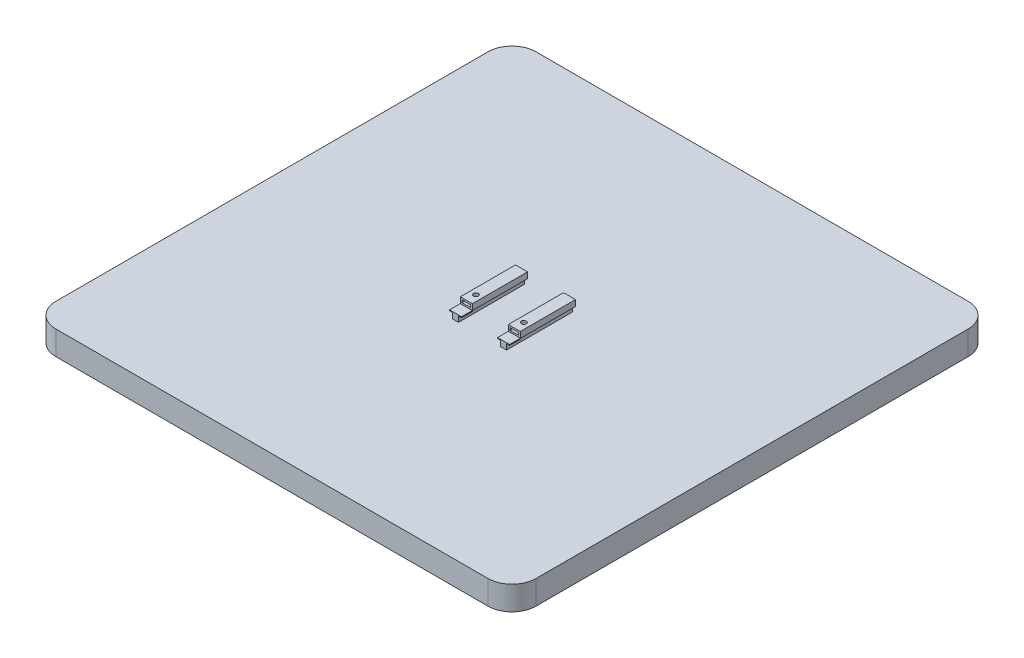
SolidWorks part; units mm, degrees
ref_plane "Front Plane" through (0, 0, 0) normal (0, 0, 1) x (1, 0, 0)
ref_plane "Top Plane" through (0, 0, 0) normal (0, 1, 0) x (1, 0, 0)
ref_plane "Right Plane" through (0, 0, 0) normal (1, 0, 0) x (0, 0, -1)
sketch "Sketch1" plane through (0, 0, 0) normal (0, 1, 0) x (1, 0, 0)
  line L1 (100, 100) -> (-100, 100)
  line L2 (100, 100) -> (100, -100)
  line L3 (100, -100) -> (-100, -100)
  line L4 (-100, 100) -> (-100, -100)
  line L5 (100, 100) -> (-100, -100) construction
  line L6 (100, -100) -> (-100, 100) construction
  point P0 (0, 0)
  dimension "D1" = 200
  dimension "D2" = 200
extrude "Boss-Extrude1" add sketch "Sketch1" along normal blind 10
ref_plane "Plane1" through (0, 0, 0) normal (0, 0, 1) x (1, 0, 0)
shell "Shell5" thickness 3
sketch "Sketch2" plane through (0, 0, 0) normal (0, 0, 1) x (1, 0, 0)
  line L0 (-11.0348, 10) -> (-11.0348, 12.6)
  line L1 (-11.0348, 12.6) -> (-12.2848, 12.6)
  line L2 (-12.2848, 12.6) -> (-12.2848, 15.1)
  line L3 (-12.2848, 15.1) -> (-7.2848, 15.1)
  line L4 (-7.2848, 15.1) -> (-7.2848, 12.6)
  line L5 (-7.2848, 12.6) -> (-8.5348, 12.6)
  line L6 (-8.5348, 12.6) -> (-8.5348, 10)
  line L7 (-8.5348, 10) -> (-11.0348, 10)
  line L8 (-9.7848, -37.9156) -> (-9.7848, 37.9156) construction
  line L9 (0.2152, -37.9156) -> (0.2152, 37.9156) construction
  line L10 (8.9652, 10) -> (11.4652, 10)
  line L11 (8.9652, 12.6) -> (8.9652, 10)
  line L12 (7.7152, 12.6) -> (8.9652, 12.6)
  line L13 (7.7152, 15.1) -> (7.7152, 12.6)
  line L14 (12.7152, 15.1) -> (7.7152, 15.1)
  line L15 (12.7152, 12.6) -> (12.7152, 15.1)
  line L16 (11.4652, 12.6) -> (12.7152, 12.6)
  line L17 (11.4652, 10) -> (11.4652, 12.6)
  line L18 (-100, 10) -> (100, 10) construction
  dimension "D1" = 2.5
  dimension "D2" = 5
  dimension "D3" = 2.5
  dimension "D4" = 2.6
  dimension "D5" = 8.75
extrude "Boss-Extrude2" add sketch "Sketch2" along normal mid plane 27.5
ref_plane "Plane2" through (0, 0, 13.75) normal (0, 0, 1) x (1, 0, 0)
sketch "Sketch5" plane through (0, 0, 13.75) normal (0, 0, 1) x (1, 0, 0)
  line L0 (-35.5496, 37.074) -> (-35.5496, 52.2233) construction
  line L1 (16.343, 12.3) -> (-35.2888, 12.3)
  line L2 (16.343, 12.3) -> (16.343, 15.1)
  line L3 (16.343, 15.1) -> (-35.2888, 15.1)
  line L4 (-35.2888, 12.3) -> (-35.2888, 15.1)
  line L5 (-9.4729, 37.074) -> (-9.4729, 52.2233) construction
  line L6 (-5.3876, 13.7) -> (-37.0511, 13.7) construction
  line L7 (-2.6881, -52.2233) -> (-2.6881, -37.074) construction
  line L8 (43.1278, -47.5797) -> (-8.504, -47.5797)
  line L9 (43.1278, -47.5797) -> (43.1278, -44.7797)
  line L10 (43.1278, -44.7797) -> (-8.504, -44.7797)
  line L11 (-8.504, -47.5797) -> (-8.504, -44.7797)
  line L12 (17.3119, -52.2233) -> (17.3119, -37.074) construction
  line L13 (21.3972, -46.1797) -> (-10.2663, -46.1797) construction
  line L14 (-7.2848, 15.1) -> (-12.2848, 15.1) construction
  dimension "D1" = 2.8
extrude "Cut-Extrude1" cut sketch "Sketch5" against normal blind 4.5
ref_plane "Plane3" through (0, 12.3, 0) normal (0, 1, 0) x (1, 0, 0)
sketch "Sketch6" plane through (0, 12.3, 0) normal (0, 1, 0) x (1, 0, 0)
  line L0 (12.7152, -13.75) -> (7.7152, -13.75)
  line L1 (12.7152, -13.75) -> (12.7152, -9.25)
  line L2 (12.7152, -9.25) -> (7.7152, -9.25)
  line L3 (7.7152, -13.75) -> (7.7152, -9.25)
  line L4 (12.7152, -13.75) -> (7.7152, -9.25) construction
  line L5 (12.7152, -9.25) -> (7.7152, -13.75) construction
  line L6 (0.2152, -2.725) -> (0.2152, 2.1712) construction
  line L7 (-12.2848, -9.25) -> (-7.2848, -9.25)
  line L8 (-7.2848, -13.75) -> (-7.2848, -9.25)
  line L9 (-12.2848, -13.75) -> (-7.2848, -13.75)
  line L10 (-12.2848, -13.75) -> (-12.2848, -9.25)
  line L11 (-11.0348, -9.25) -> (-8.5348, -9.25) construction
  line L12 (-12.2848, -9.25) -> (-12.2848, 13.75) construction
  line L13 (7.7152, -9.25) -> (7.7152, 13.75) construction
  point P0 (10.2152, -11.5)
  dimension "D1" = 4.5
  dimension "D2" = 5
extrude "Boss-Extrude3" add sketch "Sketch6" along normal blind 0.35
ref_plane "Plane4" through (0, 0, 9.25) normal (0, 0, 1) x (1, 0, 0)
sketch "Sketch7" plane through (0, 0, 9.25) normal (0, 0, 1) x (1, 0, 0)
  line L0 (10.2152, -3.777) -> (10.2152, 1.7878) construction
  line L1 (11.9652, 13.35) -> (8.4652, 13.35)
  line L2 (11.9652, 13.35) -> (11.9652, 14.35)
  line L3 (11.9652, 14.35) -> (8.4652, 14.35)
  line L4 (8.4652, 13.35) -> (8.4652, 14.35)
  line L5 (-8.0348, 13.35) -> (-11.5348, 13.35)
  line L6 (-8.0348, 13.35) -> (-8.0348, 14.35)
  line L7 (-8.0348, 14.35) -> (-11.5348, 14.35)
  line L8 (-11.5348, 13.35) -> (-11.5348, 14.35)
  line L9 (-9.7848, -3.777) -> (-9.7848, 2.6309) construction
  line L10 (15.9853, 13.85) -> (-15.357, 13.85) construction
  line L11 (-7.2848, 15.1) -> (-12.2848, 15.1) construction
  line L12 (-12.2848, 15.1) -> (-12.2848, 12.65) construction
  line L14 (7.7152, 15.1) -> (7.7152, 12.65) construction
  dimension "D1" = 1
  dimension "D2" = 3.5
  dimension "D3" = 0.75
  dimension "D4" = 0.75
  dimension "D5" = 0.75
extrude "Cut-Extrude2" cut sketch "Sketch7" against normal blind 3.5
hole_wizard "Ø2.0 (2) Diameter Hole2" positions "Sketch12" profile "Sketch13" hole size "Ø2.0" standard "ISO" end condition through all
sketch "Sketch12" plane through (0, 15.1, 0) normal (0, 1, 0) x (1, 0, 0)
  line L0 (-12.2848, -9.25) -> (-12.2848, 13.75) construction
  line L1 (7.7152, -9.25) -> (7.7152, 13.75) construction
  line L2 (-1.3475, -9.25) -> (1.3475, -9.25) construction
  line L3 (12.7152, -9.25) -> (7.7152, -9.25) construction
  point P0 (-9.7848, -5.25)
  point P2 (10.2152, -5.25)
  dimension "D1" = 2.5
  dimension "D2" = 2.5
  dimension "D3" = 4
  dimension "D4" = 4
sketch "Sketch13" plane through (-9.7848, 15.1, 5.25) normal (1, 0, 0) x (0, 0, 1)
  line L0 (0, 0) -> (0, 15.1)
  line L1 (0, 15.1) -> (1, 15.1)
  line L2 (1, 15.1) -> (1, 0)
  line L5 (1, 0) -> (0, 0)
  line L11 (0, -6.35) -> (0, 107.95) construction
  dimension "Thru Hole Dia." = 2
  dimension "Thru Hole Depth" = 15.1
sketch "Sketch14" [suppressed] plane through (0, 10, 0) normal (0, 1, 0) x (1, 0, 0)
  line L0 (-150, 150) -> (-150, -150) construction
  line L5 (-150, -150) -> (150, -150) construction
  line L6 (135, 115) -> (-115, 115)
  line L8 (135, 115) -> (135, -135)
  line L9 (135, -135) -> (-115, -135)
  line L10 (-115, 115) -> (-115, -135)
  line L11 (135, 115) -> (-115, -135) construction
  line L12 (135, -135) -> (-115, 115) construction
  point P8 (10, 115)
  point P9 (-115, -10)
  point P10 (10, -135)
  point P15 (135, -10)
  dimension "D1" = 35
  dimension "D2" = 15
  dimension "D3" = 250
  dimension "D4" = 250
pattern_sketch "Sketch-Pattern2" [suppressed]
fillet "Fillet1" radius 10 4 edges at (-100, 5, -100) (100, 5, -100) (100, 5, 100) (-100, 5, 100)
ref_plane "Plane5" through (0, 10, 0) normal (0, 1, 0) x (1, 0, 0)
